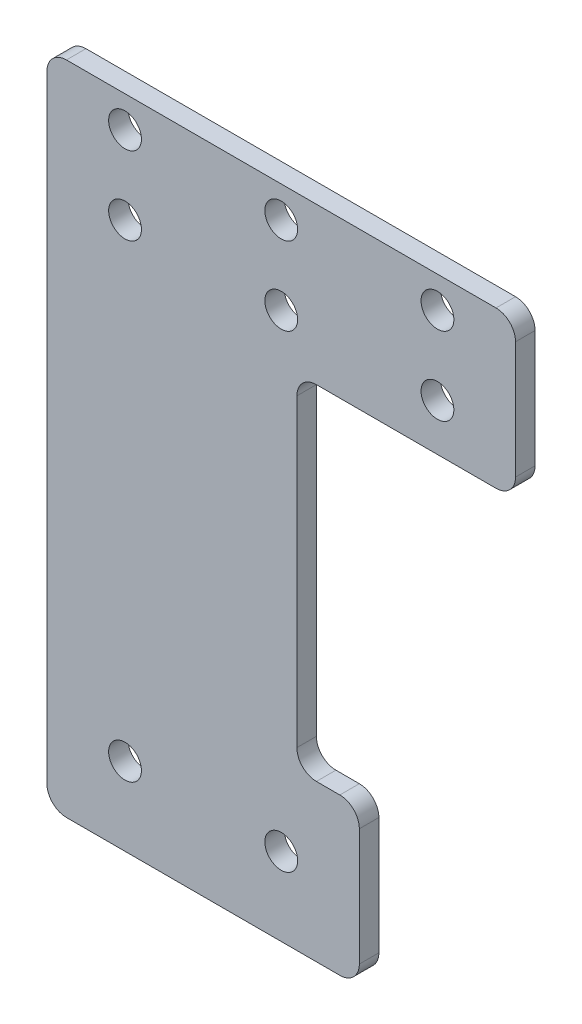
SolidWorks part; units mm, degrees
ref_plane "Front Plane" through (0, 0, 0) normal (0, 0, 1) x (1, 0, 0)
ref_plane "Top Plane" through (0, 0, 0) normal (0, 1, 0) x (1, 0, 0)
ref_plane "Right Plane" through (0, 0, 0) normal (1, 0, 0) x (0, 0, -1)
sketch "Sketch1" plane through (0, 0, 0) normal (0, 0, 1) x (1, 0, 0)
  line L0 (0, 0) -> (0, 106.68)
  line L1 (0, 106.68) -> (76.2, 106.68)
  line L2 (76.2, 106.68) -> (76.2, 81.28)
  line L3 (76.2, 81.28) -> (50.8, 81.28)
  line L4 (50.8, 81.28) -> (50.8, 0)
  line L5 (50.8, 0) -> (0, 0)
  line L6 (50.8, 81.28) -> (40.64, 81.28)
  line L7 (40.64, 81.28) -> (40.64, 0)
  line L8 (40.64, 25.4) -> (50.8, 25.4)
  circle A0 centre (12.7, 12.7) radius 2.667
  circle A1 centre (38.1, 12.7) radius 2.667
  circle A2 centre (12.7, 88.9) radius 2.667
  circle A3 centre (38.1, 88.9) radius 2.667
  circle A4 centre (63.5, 88.9) radius 2.667
  circle A5 centre (38.1, 101.6) radius 2.667
  circle A6 centre (63.5, 101.6) radius 2.667
  circle A7 centre (12.7, 101.6) radius 2.667
  dimension "D8" = 5.334
  dimension "D1" = 106.68
  dimension "D2" = 50.8
  dimension "D3" = 25.4
  dimension "D4" = 25.4
  dimension "D5" = 12.7
  dimension "D6" = 25.4
  dimension "D7" = 12.7
  dimension "D9" = 76.2
  dimension "D12" = 25.4
  dimension "D13" = 12.7
  dimension "D14" = 10.16
  dimension "D15" = 25.4
  dimension "D10" = 3
  dimension "D11" = 2
extrude "Boss-Extrude1" add sketch "Sketch1" along normal blind 3.175 contours L7 L6 L3 L2 L1 L0 L5 A7 A6 A5 A4 A3 A2 A1 A0 | A1 L7 L5 L4 L8
fillet "Fillet1" radius 3.175 8 edges at (0, 106.68, 1.5875) (76.2, 106.68, 1.5875) (76.2, 81.28, 1.5875) (50.8, 0, 1.5875) (0, 0, 1.5875) (40.64, 81.28, 1.5875) (50.8, 25.4, 1.5875) (40.64, 25.4, 1.5875)
